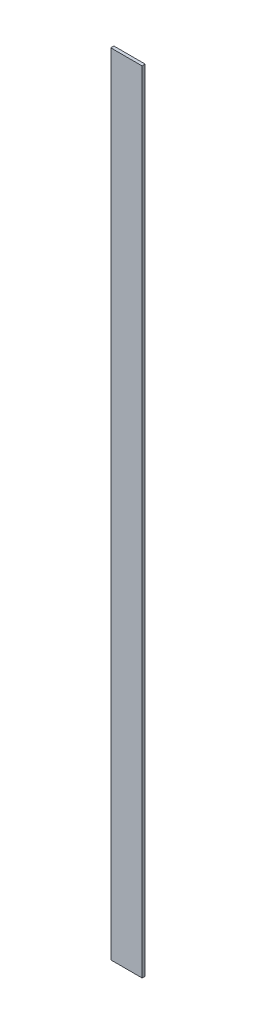
SolidWorks part; units mm, degrees
ref_plane "Front Plane" through (0, 0, 0) normal (0, 0, 1) x (1, 0, 0)
ref_plane "Top Plane" through (0, 0, 0) normal (0, 1, 0) x (1, 0, 0)
ref_plane "Right Plane" through (0, 0, 0) normal (1, 0, 0) x (0, 0, -1)
sketch "Rear wall stiffening lip profile" plane through (0, 0, 0) normal (0, 0, 1) x (1, 0, 0)
  line L0 (-139, -126) -> (-129, -126)
  line L1 (-129, -126) -> (-129, 126)
  line L2 (-129, 126) -> (-139, 126)
  line L3 (-139, 126) -> (-139, -126)
extrude "Rear wall stiffening lip" add sketch "Rear wall stiffening lip profile" along normal blind 1
